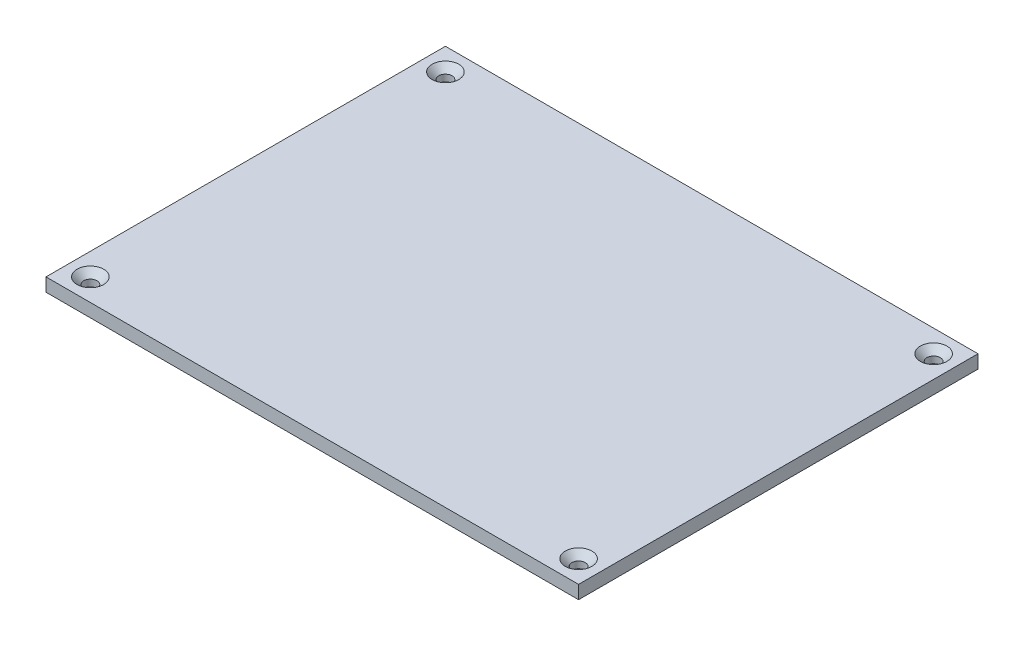
SolidWorks part; units mm, degrees
ref_plane "Front Plane" through (0, 0, 0) normal (0, 0, 1) x (1, 0, 0)
ref_plane "Top Plane" through (0, 0, 0) normal (0, 1, 0) x (1, 0, 0)
ref_plane "Right Plane" through (0, 0, 0) normal (1, 0, 0) x (0, 0, -1)
sketch "Sketch1" plane through (0, 0, 0) normal (0, 1, 0) x (1, 0, 0)
  line L1 (60, -45) -> (-60, -45)
  line L2 (60, -45) -> (60, 45)
  line L3 (60, 45) -> (-60, 45)
  line L4 (-60, -45) -> (-60, 45)
  line L5 (60, -45) -> (-60, 45) construction
  line L6 (60, 45) -> (-60, -45) construction
  line L7 (55, -40) -> (-55, -40) construction
  line L8 (55, -40) -> (55, 40) construction
  line L9 (55, 40) -> (-55, 40) construction
  line L10 (-55, -40) -> (-55, 40) construction
  line L11 (55, -40) -> (-55, 40) construction
  line L12 (55, 40) -> (-55, -40) construction
  circle A0 centre (-55, 40) radius 1.5
  circle A1 centre (-55, -40) radius 1.5
  circle A2 centre (55, -40) radius 1.5
  circle A3 centre (55, 40) radius 1.5
  point P0 (0, 0)
  point P6 (0, 0)
  dimension "D3" = 3
  dimension "D1" = 110
  dimension "D2" = 80
  dimension "D4" = 5
  dimension "D5" = 5
extrude "Boss-Extrude1" add sketch "Sketch1" along normal blind 3
chamfer "Chamfer1" distance 1.5 angle 45 4 edges at (55, 3, -38.5) (55, 3, 41.5) (-55, 3, 41.5) (-55, 3, -38.5)
